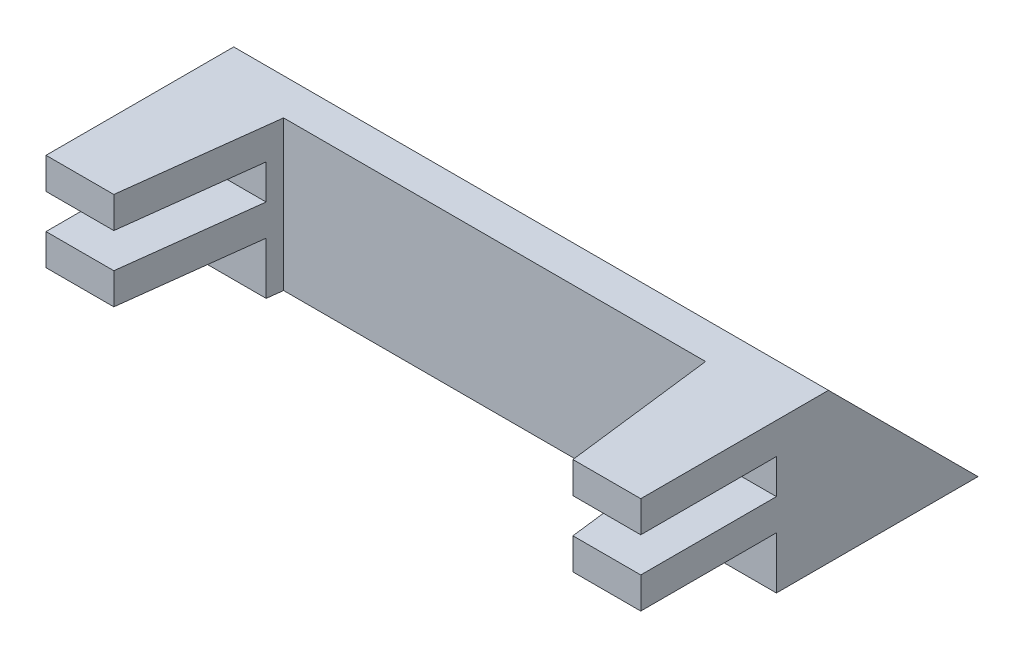
SolidWorks part; units mm, degrees
ref_plane "Front Plane" through (0, 0, 0) normal (0, 0, 1) x (1, 0, 0)
ref_plane "Top Plane" through (0, 0, 0) normal (0, 1, 0) x (1, 0, 0)
ref_plane "Right Plane" through (0, 0, 0) normal (1, 0, 0) x (0, 0, -1)
sketch "Sketch1" plane through (0, 0, 0) normal (1, 0, 0) x (0, 0, -1)
  line L0 (0, 0) -> (19.32, 0)
  line L1 (19.32, 0) -> (4.99, 14.33)
  line L2 (4.99, 14.33) -> (-13, 14.33)
  line L3 (-13, 14.33) -> (-13, 11.33)
  line L4 (-13, 11.33) -> (0, 11.33)
  line L5 (0, 11.33) -> (0, 8)
  line L6 (0, 8) -> (-13, 8)
  line L7 (-13, 8) -> (-13, 5)
  line L8 (-13, 5) -> (0, 5)
  line L9 (0, 5) -> (0, 0)
  dimension "D1" = 45
  dimension "D2" = 19.32
  dimension "D3" = 8
  dimension "D4" = 3.33
  dimension "D5" = 3
  dimension "D6" = 13
extrude "Boss-Extrude1" add sketch "Sketch1" against normal blind 57 contours L1 L2 L3 L4 L5 L6 L7 L8 L9 L0
sketch "Sketch2" plane through (0, 14.33, 0) normal (0, 1, 0) x (1, 0, 0)
  line L0 (-6.5, -13) -> (-8.2791, 1.49)
  line L1 (-57, -13) -> (0, -13) construction
  line L2 (-8.2791, 1.49) -> (-48.7209, 1.49)
  line L3 (-48.7209, 1.49) -> (-50.5, -13)
  line L4 (-50.5, -13) -> (-6.5, -13)
  line L5 (-57, 4.99) -> (0, 4.99) construction
  line L6 (-28.5, -13) -> (-28.5, 1.49) construction
  dimension "D1" = 83
  dimension "D2" = 3.5
  dimension "D3" = 6.5
extrude "Cut-Extrude1" cut sketch "Sketch2" against normal up to next
sketch "Sketch3" plane through (0, 9.66, -9.66) normal (0, 0.7071, -0.7071) x (1, 0, 0)
  line L0 (-57, 13.6613) -> (-57, -6.6044) construction
  line L1 (-57, 9.2678) -> (0, 9.2678)
  line L2 (-57, 9.2678) -> (-57, -5.8822)
  line L3 (-57, -5.8822) -> (0, -5.8822)
  line L4 (0, 9.2678) -> (0, -5.8822)
  line L5 (0, 13.6613) -> (0, -6.6044) construction
  dimension "D1" = 15.15
extrude "Cut-Extrude2" [suppressed] cut sketch "Sketch3" against normal blind 1.15
